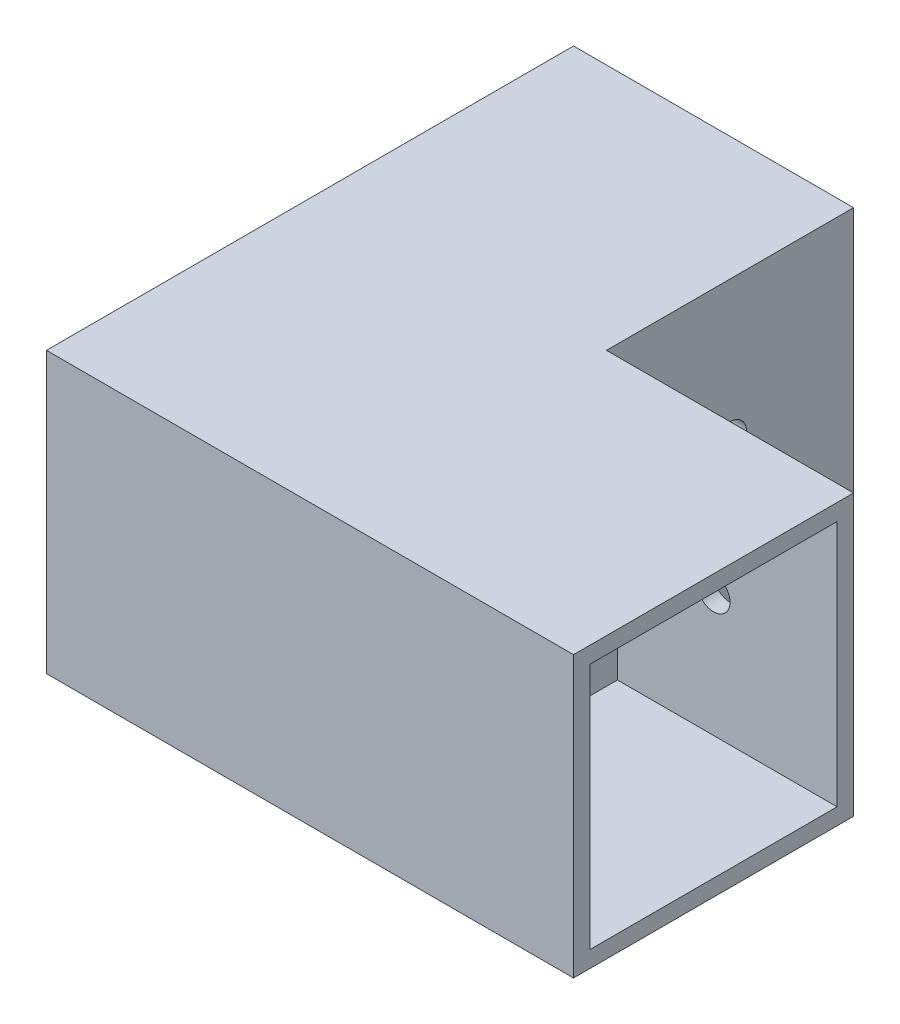
SolidWorks part; units mm, degrees
ref_plane "Front Plane" through (0, 0, 0) normal (0, 0, 1) x (1, 0, 0)
ref_plane "Top Plane" through (0, 0, 0) normal (0, 1, 0) x (1, 0, 0)
ref_plane "Right Plane" through (0, 0, 0) normal (1, 0, 0) x (0, 0, -1)
sketch "Sketch1" plane through (0, 0, 0) normal (0, 1, 0) x (1, 0, 0)
  line L0 (0, 0) -> (0, 90) construction
  line L1 (0, 90) -> (45, 90) construction
  line L2 (45, 90) -> (45, 45) construction
  line L3 (45, 45) -> (90, 45) construction
  line L4 (90, 45) -> (90, 0) construction
  line L5 (90, 0) -> (0, 0) construction
  line L6 (-3, -3) -> (-3, 93)
  line L7 (-3, 93) -> (48, 93)
  line L8 (48, 93) -> (48, 48)
  line L9 (48, 48) -> (93, 48)
  line L10 (93, 48) -> (93, -3)
  line L11 (93, -3) -> (-3, -3)
  dimension "D1" = 45
  dimension "D2" = 45
  dimension "D3" = 90
  dimension "D4" = 90
  dimension "D5" = 3
extrude "Boss-Extrude1" add sketch "Sketch1" along normal blind 51
sketch "Sketch2" plane through (93, 0, 0) normal (1, 0, 0) x (0, 0, -1)
  line L0 (45, 3) -> (45, 48)
  line L1 (45, 48) -> (0, 48)
  line L2 (0, 48) -> (0, 3)
  line L3 (0, 3) -> (45, 3)
  line L4 (-3, 0) -> (48, 0)
  line L5 (48, 0) -> (48, 51)
  line L6 (48, 51) -> (-3, 51)
  line L7 (-3, 51) -> (-3, 0)
  line L8 (-3, 0) -> (48, 0) construction
  line L9 (48, 0) -> (48, 51) construction
  line L10 (48, 51) -> (-3, 51) construction
  line L11 (-3, 51) -> (-3, 0) construction
  dimension "D1" = 0
  dimension "D2" = 3
extrude "Cut-Extrude1" cut sketch "Sketch2" against normal blind 40
sketch "Sketch3" plane through (0, 0, -93) normal (0, 0, -1) x (-1, 0, 0)
  line L0 (0, 3) -> (0, 48)
  line L1 (0, 48) -> (-45, 48)
  line L2 (-45, 48) -> (-45, 3)
  line L3 (-45, 3) -> (0, 3)
  line L4 (-48, 0) -> (3, 0)
  line L5 (3, 0) -> (3, 51)
  line L6 (3, 51) -> (-48, 51)
  line L7 (-48, 51) -> (-48, 0)
  line L8 (-48, 0) -> (3, 0) construction
  line L9 (3, 0) -> (3, 51) construction
  line L10 (3, 51) -> (-48, 51) construction
  line L11 (-48, 51) -> (-48, 0) construction
  dimension "D1" = 0
  dimension "D2" = 3
extrude "Cut-Extrude2" cut sketch "Sketch3" against normal blind 40
sketch "Sketch4" plane through (0, 0, -48) normal (0, 0, -1) x (-1, 0, 0)
  line L0 (-70.5, 0) -> (-70.5, 51) construction
  line L1 (-93, 0) -> (-48, 0) construction
  line L2 (-93, 51) -> (-48, 51) construction
  circle A0 centre (-70.5, 25.5) radius 3
  dimension "D1" = 6
extrude "Cut-Extrude3" cut sketch "Sketch4" against normal up to next
sketch "Sketch5" plane through (48, 0, 0) normal (1, 0, 0) x (0, 0, -1)
  line L0 (70.5, 51) -> (70.5, 0) construction
  line L1 (48, 51) -> (93, 51) construction
  line L2 (48, 0) -> (93, 0) construction
  circle A0 centre (70.5, 25.5) radius 3
  dimension "D1" = 6
extrude "Cut-Extrude4" cut sketch "Sketch5" against normal up to next
